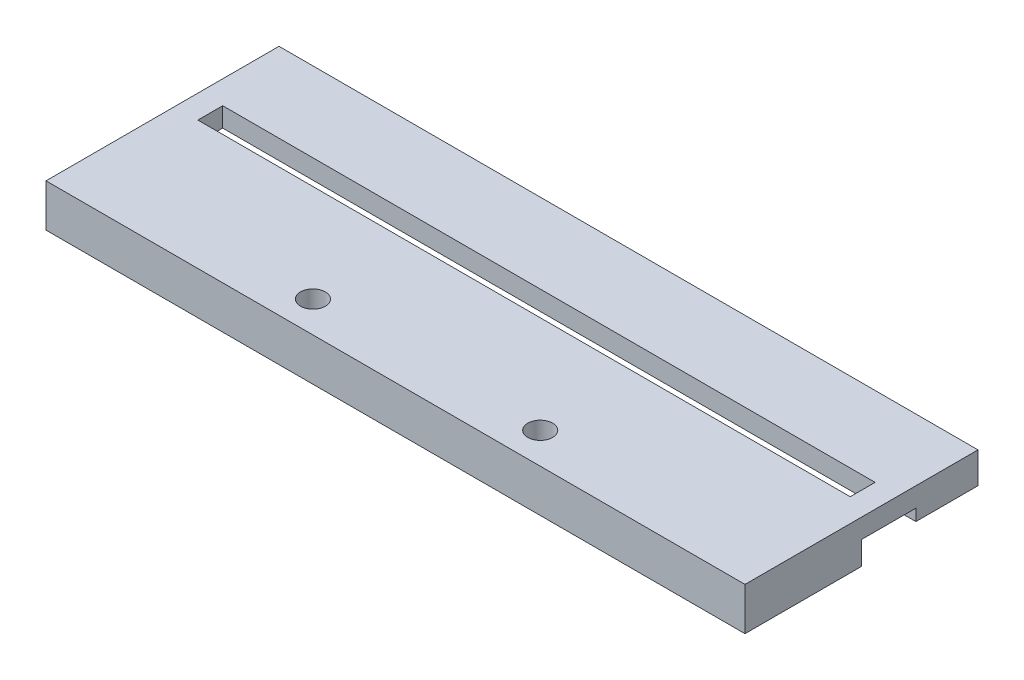
SolidWorks part; units mm, degrees
ref_plane "Front Plane" through (0, 0, 0) normal (0, 0, 1) x (1, 0, 0)
ref_plane "Top Plane" through (0, 0, 0) normal (0, 1, 0) x (1, 0, 0)
ref_plane "Right Plane" through (0, 0, 0) normal (1, 0, 0) x (0, 0, -1)
sketch "Sketch2" plane through (0, 0, 0) normal (0, 1, 0) x (1, 0, 0)
  line L1 (-45, -15) -> (45, -15)
  line L2 (-45, -15) -> (-45, 15)
  line L3 (-45, 15) -> (45, 15)
  line L4 (45, -15) -> (45, 15)
  line L5 (-45, -15) -> (45, 15) construction
  line L6 (-45, 15) -> (45, -15) construction
  point P0 (0, 0)
  dimension "D1" = 90
  dimension "D2" = 30
extrude "Boss-Extrude1" add sketch "Sketch2" along normal blind 5.5
sketch "Sketch3" plane through (0, 0, 0) normal (0, -1, 0) x (1, 0, 0)
  line L0 (45, 15) -> (45, -15) construction
  line L1 (-45, -10) -> (45, -10)
  line L2 (-45, -10) -> (-45, -7)
  line L3 (-45, -7) -> (45, -7)
  line L4 (45, -10) -> (45, -7)
  line L5 (-45, -10) -> (45, -7) construction
  line L6 (-45, -7) -> (45, -10) construction
  line L8 (45, -15) -> (-45, -15) construction
  point P0 (0, -8.5)
  point P9 (0, 0)
  dimension "D1" = 3
  dimension "D2" = 5
extrude "Cut-Extrude1" cut sketch "Sketch3" against normal blind 1.5
sketch "Sketch4" plane through (0, 0, -15) normal (0, 0, -1) x (-1, 0, 0)
  line L0 (-45, 0) -> (45, 0) construction
  line L1 (-42.5, 1.5) -> (42.5, 1.5)
  line L2 (-42.5, 1.5) -> (-42.5, 3)
  line L3 (-42.5, 3) -> (42.5, 3)
  line L4 (42.5, 1.5) -> (42.5, 3)
  line L5 (-42.5, 1.5) -> (42.5, 3) construction
  line L6 (-42.5, 3) -> (42.5, 1.5) construction
  line L7 (45, 5.5) -> (45, 0) construction
  point P0 (0, 2.25)
  dimension "D1" = 1.5
  dimension "D2" = 1.5
  dimension "D3" = 2.5
extrude "Cut-Extrude2" cut sketch "Sketch4" against normal blind 15
sketch "Sketch5" plane through (0, 5.5, 0) normal (0, 1, 0) x (1, 0, 0)
  line L1 (-42, 1.55) -> (42, 1.55)
  line L2 (-42, 1.55) -> (-42, 4.75)
  line L3 (-42, 4.75) -> (42, 4.75)
  line L4 (42, 1.55) -> (42, 4.75)
  line L5 (-42, 1.55) -> (42, 4.75) construction
  line L6 (-42, 4.75) -> (42, 1.55) construction
  line L7 (45, 7) -> (-45, 7) construction
  line L8 (45, -15) -> (45, 15) construction
  point P0 (0, 3.15)
  point P9 (0, 0)
  dimension "D1" = 3.85
  dimension "D2" = 3.2
  dimension "D3" = 3
extrude "Cut-Extrude3" cut sketch "Sketch5" against normal up to surface (2.5 mm away) up to face at (0, 3, -7.5)
sketch "Sketch6" plane through (0, 5.5, 0) normal (0, 1, 0) x (1, 0, 0)
  line L1 (-45, -15) -> (45, -15) construction
  circle A0 centre (-14.633, -11) radius 1.6
  circle A1 centre (14.633, -11) radius 1.6
  point P7 (0, 0)
  point P8 (0, 0)
  dimension "D1" = 3.2
  dimension "D2" = 3.2
  dimension "D5" = 4
  dimension "D3" = 29.266
  dimension "D4" = 14.633
extrude "Cut-Extrude4" cut sketch "Sketch6" against normal through all
sketch "Sketch7" plane through (0, 0, -15) normal (0, 0, -1) x (-1, 0, 0)
  line L1 (-45, 0) -> (45, 0)
  line L2 (-45, 0) -> (-45, 1.5)
  line L3 (-45, 1.5) -> (45, 1.5)
  line L4 (45, 0) -> (45, 1.5)
  line L5 (-45, 0) -> (45, 1.5) construction
  line L6 (-45, 1.5) -> (45, 0) construction
  line L8 (-45, 5.5) -> (-45, 0) construction
  line L9 (45, 5.5) -> (45, 0) construction
  point P0 (0, 0.75)
extrude "Cut-Extrude5" cut sketch "Sketch7" against normal up to surface (5 mm away) up to face at (0, 1, -10)
sketch "Sketch8" plane through (0, 0, 0) normal (0, -1, 0) x (-1, 0, 0)
  line L0 (45, 7) -> (45, -15) construction
  line L1 (-45, 0) -> (45, 0)
  line L2 (-45, 0) -> (-45, 7)
  line L3 (-45, 7) -> (45, 7)
  line L4 (45, 0) -> (45, 7)
  line L5 (-45, 0) -> (45, 7) construction
  line L6 (-45, 7) -> (45, 0) construction
  line L7 (42.5, 0) -> (-42.5, 0) construction
  line L8 (-45, 7) -> (45, 7) construction
  point P0 (0, 3.5)
extrude "Cut-Extrude6" cut sketch "Sketch8" against normal up to surface (3 mm away) up to face at (0, 3, -3.15)
